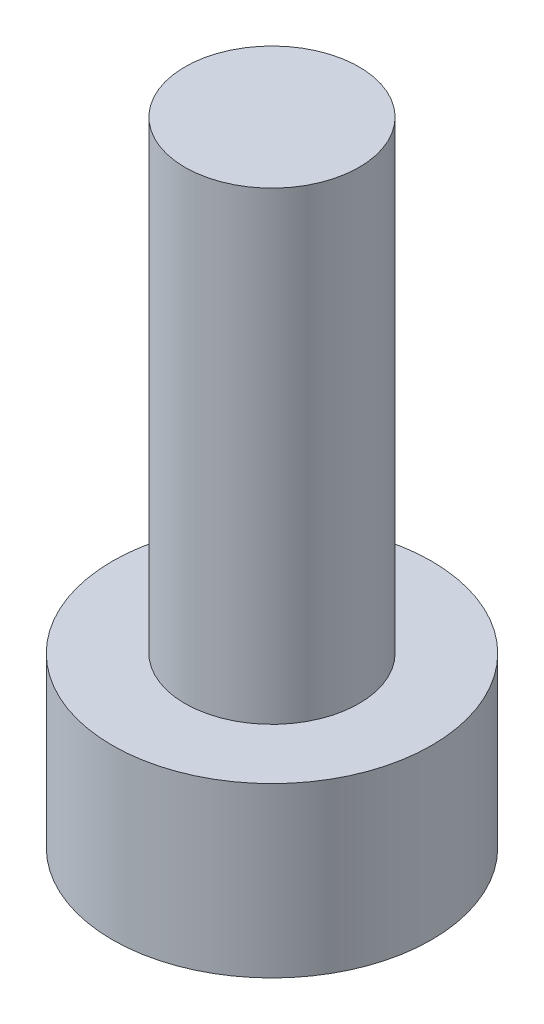
SolidWorks part; units mm, degrees
material "铸造碳钢"
ref_plane "前视基准面" through (0, 0, 0) normal (0, 0, 1) x (1, 0, 0)
ref_plane "上视基准面" through (0, 0, 0) normal (0, 1, 0) x (1, 0, 0)
ref_plane "右视基准面" through (0, 0, 0) normal (1, 0, 0) x (0, 0, -1)
other "Configuration Table"
sketch "草图1" plane through (0, 0, 0) normal (0, 1, 0) x (1, 0, 0)
  circle A0 centre (0, 0) radius 1.5
  dimension "D1" = 3
extrude "凸台-拉伸1" add sketch "草图1" along normal blind 8
sketch "草图2" plane through (0, 0, 0) normal (0, -1, 0) x (1, 0, 0)
  circle A0 centre (0, 0) radius 2.75
  dimension "D1" = 5.5
extrude "凸台-拉伸2" add sketch "草图2" along normal blind 2.9
sketch "草图3" plane through (0, -2.9, 0) normal (0, -1, 0) x (1, 0, 0)
  line L0 (0, 0) -> (0, 2.8092) construction
  line L1 (1.25, 0.7217) -> (0, 1.4434)
  line L2 (0, 1.4434) -> (-1.25, 0.7217)
  line L3 (-1.25, 0.7217) -> (-1.25, -0.7217)
  line L4 (-1.25, -0.7217) -> (0, -1.4434)
  line L5 (0, -1.4434) -> (1.25, -0.7217)
  line L6 (1.25, -0.7217) -> (1.25, 0.7217)
  circle A0 centre (0, 0) radius 1.25 construction
  dimension "D1" = 2.5
extrude "切除-拉伸1" cut sketch "草图3" against normal blind 1.5
